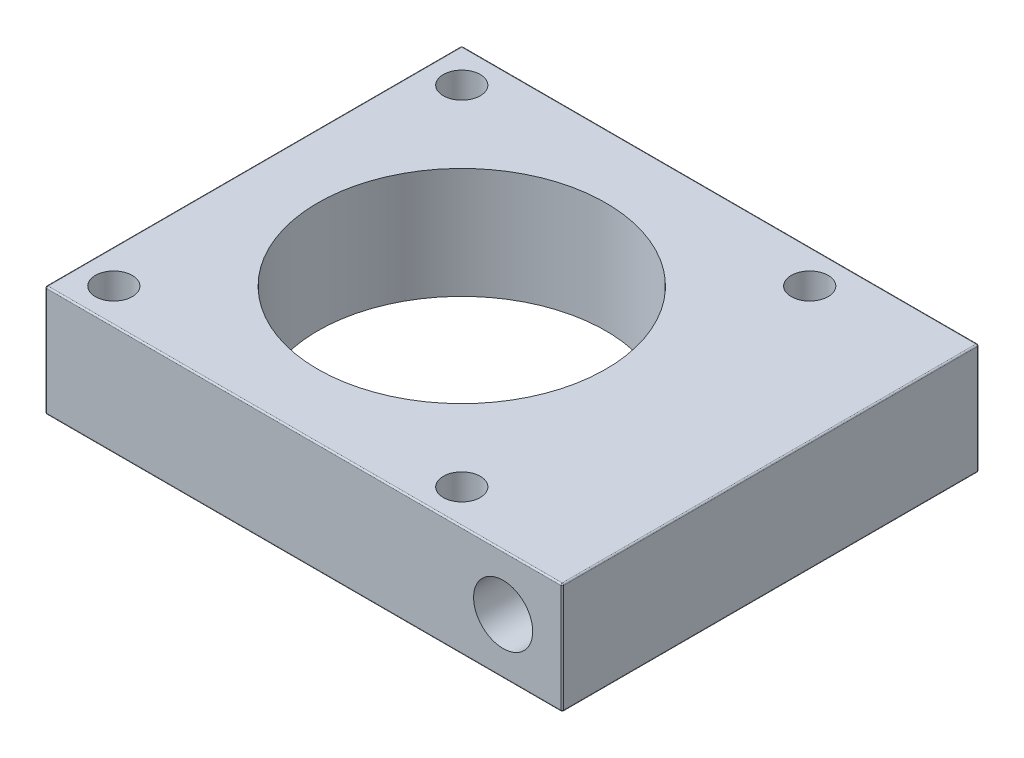
SolidWorks part; units mm, degrees
material "1060 Alloy"
ref_plane "Front Plane" through (0, 0, 0) normal (0, 0, 1) x (1, 0, 0)
ref_plane "Top Plane" through (0, 0, 0) normal (0, 1, 0) x (1, 0, 0)
ref_plane "Right Plane" through (0, 0, 0) normal (1, 0, 0) x (0, 0, -1)
sketch "Sketch1" plane through (0, 0, 0) normal (0, 0, 1) x (1, 0, 0)
  line L1 (0, 0) -> (70, 0)
  line L2 (0, 0) -> (0, 15)
  line L3 (0, 15) -> (70, 15)
  line L4 (70, 0) -> (70, 15)
  circle A0 centre (62, 7.5) radius 4
  point P8 (70, 7.5)
  dimension "D3" = 8
  dimension "D1" = 70
  dimension "D2" = 15
  dimension "D4" = 0
  dimension "D5" = 8
extrude "Boss-Extrude1" add sketch "Sketch1" along normal blind 56.4
sketch "Sketch2" plane through (0, 15, 0) normal (0, 1, 0) x (1, 0, 0)
  line L0 (0, -56.4) -> (0, 0) construction
  circle A0 centre (28.2, -28.2) radius 19.5
  point P5 (0, -28.2)
  dimension "D1" = 39
  dimension "D2" = 28.2
extrude "Cut-Extrude1" cut sketch "Sketch2" against normal blind 42.3
sketch "Sketch3" plane through (0, 0, 0) normal (0, -1, 0) x (-1, 0, 0)
  line L1 (-51.75, -4.65) -> (-4.65, -4.65)
  line L2 (-51.75, -4.65) -> (-51.75, -51.75)
  line L3 (-51.75, -51.75) -> (-4.65, -51.75)
  line L4 (-4.65, -4.65) -> (-4.65, -51.75)
  line L5 (-51.75, -4.65) -> (-4.65, -51.75) construction
  line L6 (-51.75, -51.75) -> (-4.65, -4.65) construction
  circle A0 centre (-51.75, -4.65) radius 2.5
  circle A1 centre (-4.65, -4.65) radius 2.5
  circle A2 centre (-4.65, -51.75) radius 2.5
  circle A3 centre (-51.75, -51.75) radius 2.5
  point P0 (-28.2, -28.2)
  dimension "D3" = 5
  dimension "D4" = 5
  dimension "D5" = 5
  dimension "D6" = 5
  dimension "D1" = 47.1
  dimension "D2" = 47.1
extrude "Cut-Extrude2" cut sketch "Sketch3" against normal through all contours A0 | A3 | A2 | A1
fillet "Fillet1" radius 0.2 12 edges at (70, 7.5, 56.4) (70, 7.5, 0) (0, 7.5, 0) (0, 0, 28.2) (0, 15, 28.2) (0, 7.5, 56.4) (35, 0, 56.4) (35, 15, 56.4) (70, 15, 28.2) (70, 0, 28.2) (35, 0, 0) (35, 15, 0)
